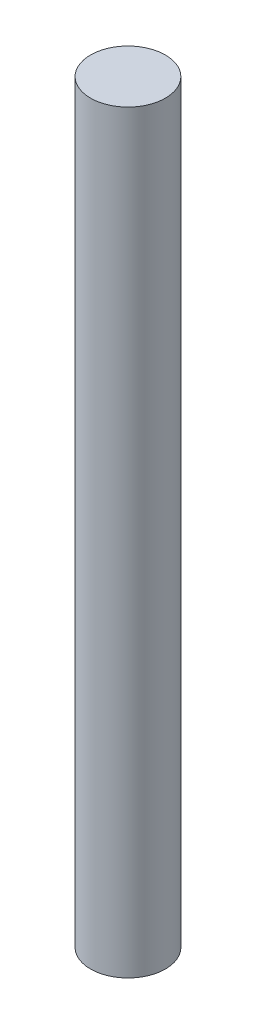
SolidWorks part; units mm, degrees
ref_plane "Front" through (0, 0, 0) normal (0, 0, 1) x (1, 0, 0)
ref_plane "Top" through (0, 0, 0) normal (0, 1, 0) x (1, 0, 0)
ref_plane "Right" through (0, 0, 0) normal (1, 0, 0) x (0, 0, -1)
sketch "Sketch1" plane through (0, 0, 0) normal (0, 1, 0) x (1, 0, 0)
  circle A0 centre (0, 0) radius 9.525
  dimension "D1" = 19.05
extrude "Boss-Extrude1" add sketch "Sketch1" along normal blind 192
